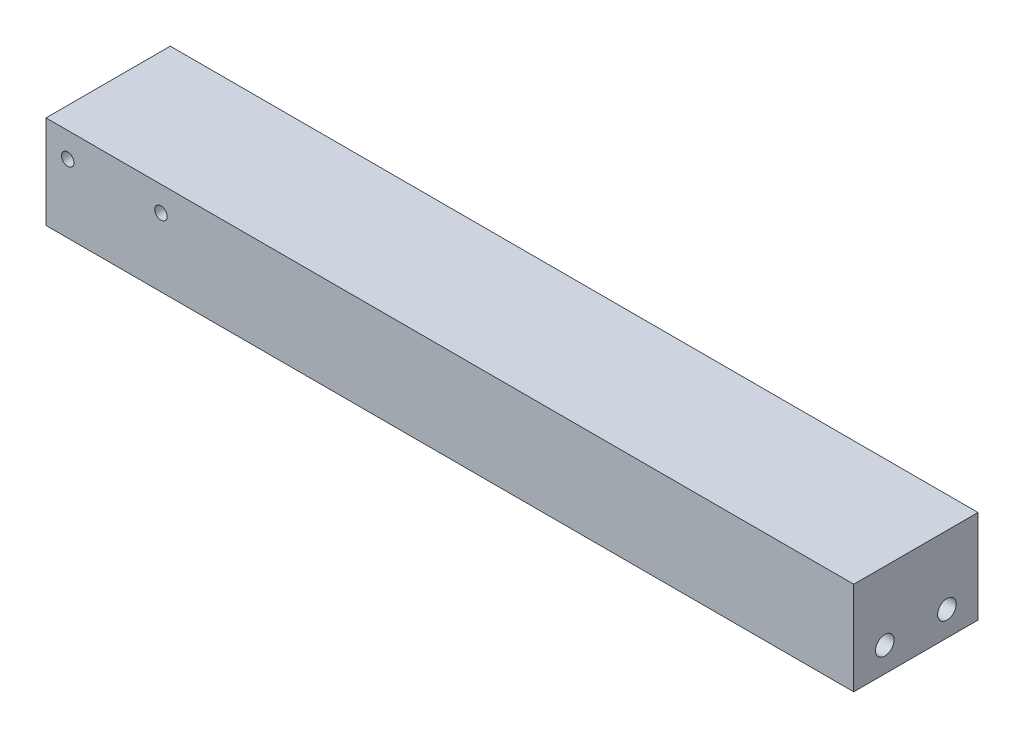
SolidWorks part; units mm, degrees
ref_plane "Front Plane" through (0, 0, 0) normal (0, 0, 1) x (1, 0, 0)
ref_plane "Top Plane" through (0, 0, 0) normal (0, 1, 0) x (1, 0, 0)
ref_plane "Right Plane" through (0, 0, 0) normal (1, 0, 0) x (0, 0, -1)
sketch "Sketch1" plane through (0, 0, 0) normal (0, 0, 1) x (1, 0, 0)
  line L1 (0, 0) -> (260, 0)
  line L2 (0, 0) -> (0, 30)
  line L3 (0, 30) -> (260, 30)
  line L4 (260, 0) -> (260, 30)
  dimension "D1" = 30
  dimension "D2" = 260
extrude "Boss-Extrude1" add sketch "Sketch1" along normal blind 40
sketch "Esquisse1" plane through (0, 0, 40) normal (0, 0, 1) x (1, 0, 0)
  line L1 (260, 30) -> (0, 30) construction
  line L2 (0, 30) -> (0, 0) construction
  circle A0 centre (7, 22) radius 2
  circle A1 centre (37, 22) radius 2
  dimension "D1" = 30
  dimension "D2" = 7
  dimension "D3" = 8
  dimension "D4" = 4
extrude "Enlèv. mat.-Extru.1" cut sketch "Esquisse1" against normal through all
sketch "Esquisse2" plane through (260, 0, 0) normal (1, 0, 0) x (0, 0, -1)
  line L0 (0, 0) -> (0, 30) construction
  line L1 (-40, 0) -> (0, 0) construction
  circle A0 centre (-10, 8) radius 3
  circle A1 centre (-30, 8) radius 3
  dimension "D1" = 20
  dimension "D2" = 10
  dimension "D3" = 6
  dimension "D4" = 8
extrude "Enlèv. mat.-Extru.2" cut sketch "Esquisse2" against normal through all
